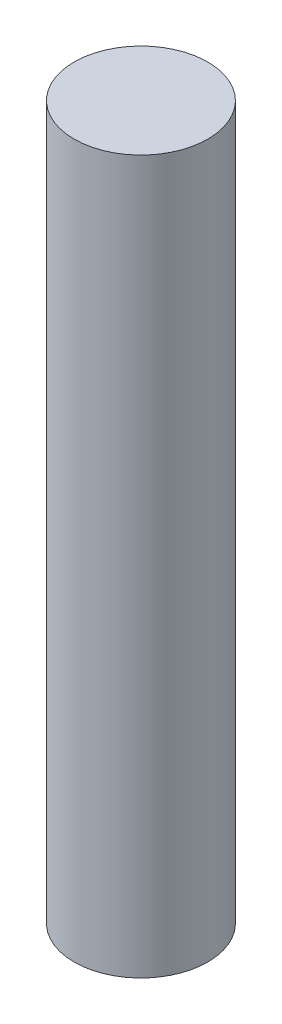
SolidWorks part; units mm, degrees
ref_plane "Ön Düzlem" through (0, 0, 0) normal (0, 0, 1) x (1, 0, 0)
ref_plane "Üst Düzlem" through (0, 0, 0) normal (0, 1, 0) x (1, 0, 0)
ref_plane "Sağ Düzlem" through (0, 0, 0) normal (1, 0, 0) x (0, 0, -1)
sketch "Çizim1" plane through (0, 0, 0) normal (0, 1, 0) x (1, 0, 0)
  circle A0 centre (0, 0) radius 7.5
  dimension "D1" = 15
extrude "Yükseklik-Ekstrüzyon1" add sketch "Çizim1" along normal blind 80
